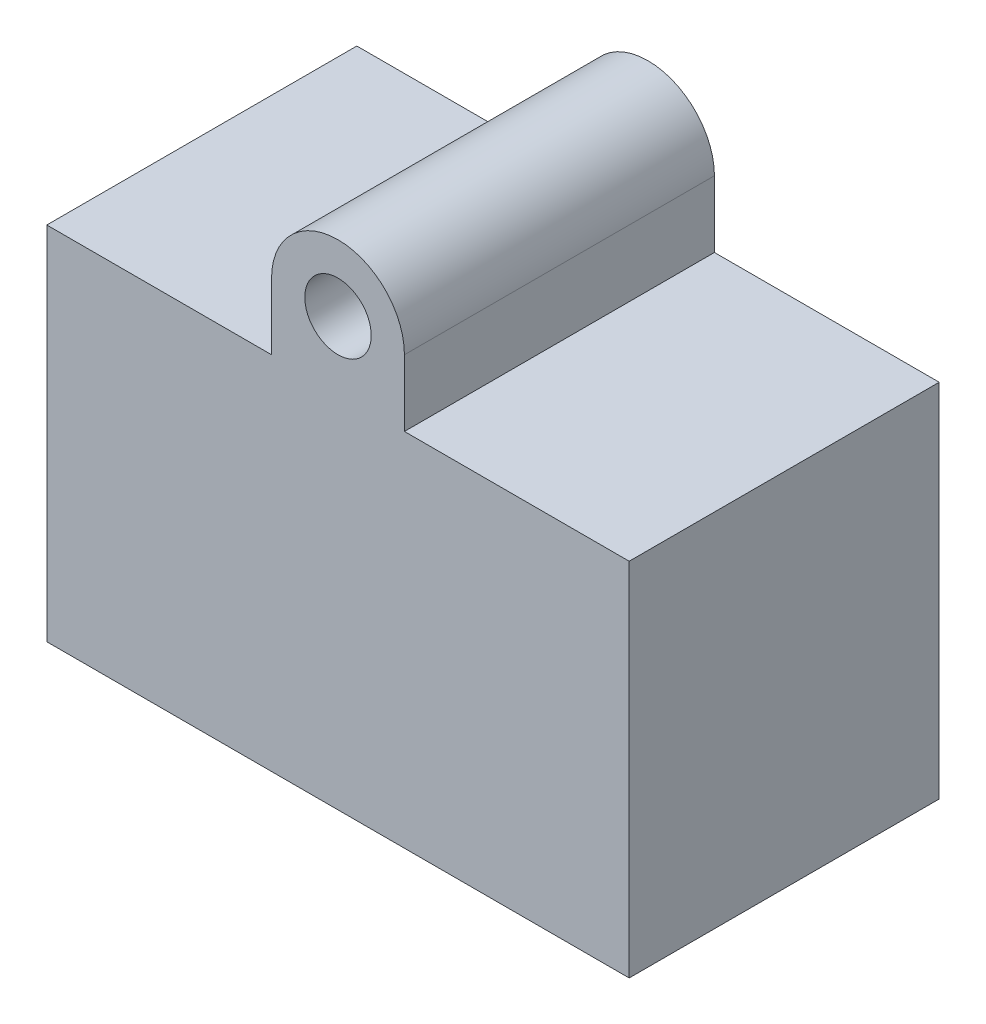
SolidWorks part; units mm, degrees
ref_plane "Front Plane" through (0, 0, 0) normal (0, 0, 1) x (1, 0, 0)
ref_plane "Top Plane" through (0, 0, 0) normal (0, 1, 0) x (1, 0, 0)
ref_plane "Right Plane" through (0, 0, 0) normal (1, 0, 0) x (0, 0, -1)
sketch "Sketch1" plane through (0, 0, 0) normal (0, 0, 1) x (1, 0, 0)
  line L0 (0, 0) -> (0, 2.575) construction
  line L1 (0, 2.575) -> (0, -2.575) construction
  line L2 (0, -2.575) -> (-5.08, -2.575) construction
  line L3 (-5.08, -2.575) -> (5.07, -2.575) construction
  line L4 (-5.08, 2.575) -> (-6.58, 2.575) construction
  line L5 (-5.08, 2.575) -> (5.07, 2.575)
  line L6 (-5.08, 2.575) -> (-5.08, -2.575)
  line L7 (-5.08, -2.575) -> (5.07, -2.575)
  line L8 (5.07, 2.575) -> (5.07, -2.575)
  line L9 (-6.58, 2.575) -> (-6.58, 4.075) construction
  line L10 (5.07, -2.575) -> (6.57, -2.575) construction
  line L11 (6.57, -2.575) -> (6.57, -4.075) construction
  line L12 (-0.005, 4.075) -> (-0.005, 6.075) construction
  line L13 (-6.58, 4.075) -> (-1.505, 4.075)
  line L14 (-6.58, 4.075) -> (-6.58, -4.075)
  line L15 (-6.58, -4.075) -> (6.57, -4.075)
  line L16 (6.57, 4.075) -> (6.57, -4.075)
  line L17 (-0.005, 6.075) -> (-0.005, 5.075) construction
  line L20 (1.495, 4.075) -> (6.57, 4.075)
  line L21 (-0.005, 4.075) -> (-0.005, 7.075) construction
  line L22 (-0.005, 7.075) -> (-0.005, 5.575) construction
  line L23 (-1.505, 5.575) -> (-1.505, 4.075)
  line L24 (1.495, 5.575) -> (1.495, 4.075)
  circle A2 centre (-0.005, 5.575) radius 0.75
  arc A3 (1.495, 5.575) -> (-1.505, 5.575) centre (-0.005, 5.575) ccw
  dimension "D10" = 1.5
  dimension "D11" = 3
  dimension "D12" = 3
  dimension "D1" = 2.575
  dimension "D2" = 5.15
  dimension "D3" = 5.08
  dimension "D4" = 10.15
  dimension "D5" = 1.5
  dimension "D6" = 1.5
  dimension "D7" = 1.5
  dimension "D8" = 1.5
  dimension "D9" = 2
extrude "Boss-Extrude1" add sketch "Sketch1" along normal blind 7
sketch "Sketch2" plane through (0, 0, 7) normal (0, 0, 1) x (1, 0, 0)
  line L1 (-6.58, 4.075) -> (6.57, 4.075)
  line L2 (-6.58, 4.075) -> (-6.58, -4.075)
  line L3 (-6.58, -4.075) -> (6.57, -4.075)
  line L4 (6.57, 4.075) -> (6.57, -4.075)
extrude "Boss-Extrude2" add sketch "Sketch2" against normal blind 2
